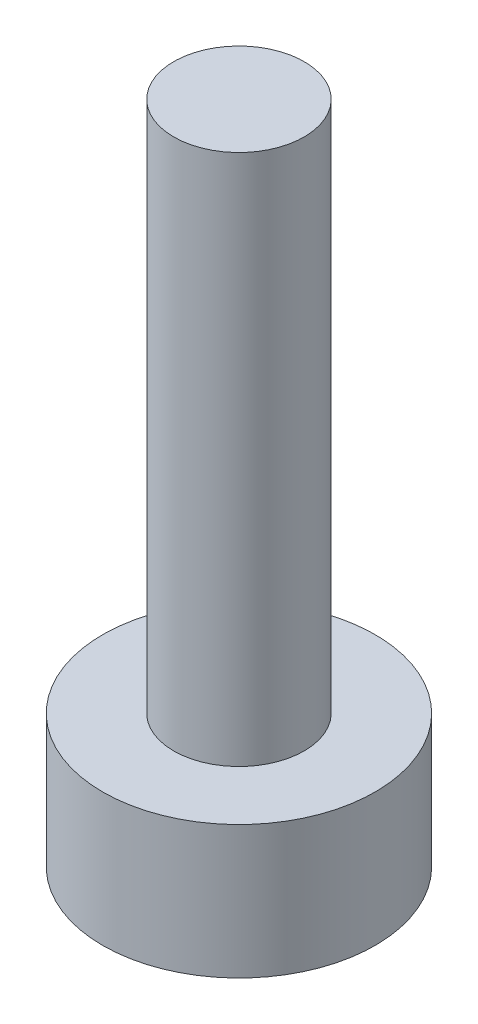
SolidWorks part; units mm, degrees
ref_plane "Front Plane" through (0, 0, 0) normal (0, 0, 1) x (1, 0, 0)
ref_plane "Top Plane" through (0, 0, 0) normal (0, 1, 0) x (1, 0, 0)
ref_plane "Right Plane" through (0, 0, 0) normal (1, 0, 0) x (0, 0, -1)
sketch "Sketch1" plane through (0, 0, 0) normal (0, 1, 0) x (1, 0, 0)
  circle A0 centre (0, 0) radius 5.125
extrude "Boss-Extrude1" add sketch "Sketch1" along normal blind 5 contours A0
sketch "Sketch2" plane through (0, 5, 0) normal (0, 1, 0) x (1, 0, 0)
  circle A0 centre (0, 0) radius 2.454
extrude "Boss-Extrude2" add sketch "Sketch2" along normal blind 20
sketch "Sketch3" plane through (0, 0, 0) normal (0, -1, 0) x (1, 0, 0)
  line L0 (-2.4577, 3.4588) -> (2.4577, 3.4588)
  line L1 (0, -5.6375) -> (0, 5.6375) construction
  line L2 (2.4577, 3.4588) -> (4.099, 0)
  line L3 (5.6375, 0) -> (-5.6375, 0) construction
  line L4 (2.4577, -3.4588) -> (4.099, 0)
  line L5 (-2.4577, -3.4588) -> (2.4577, -3.4588)
  line L6 (-2.4577, -3.4588) -> (-4.099, 0)
  line L7 (-2.4577, 3.4588) -> (-4.099, 0)
  point P10 (0, -3.4588)
  point P12 (0, 3.4588)
extrude "Cut-Extrude1" cut sketch "Sketch3" against normal blind 1.5
